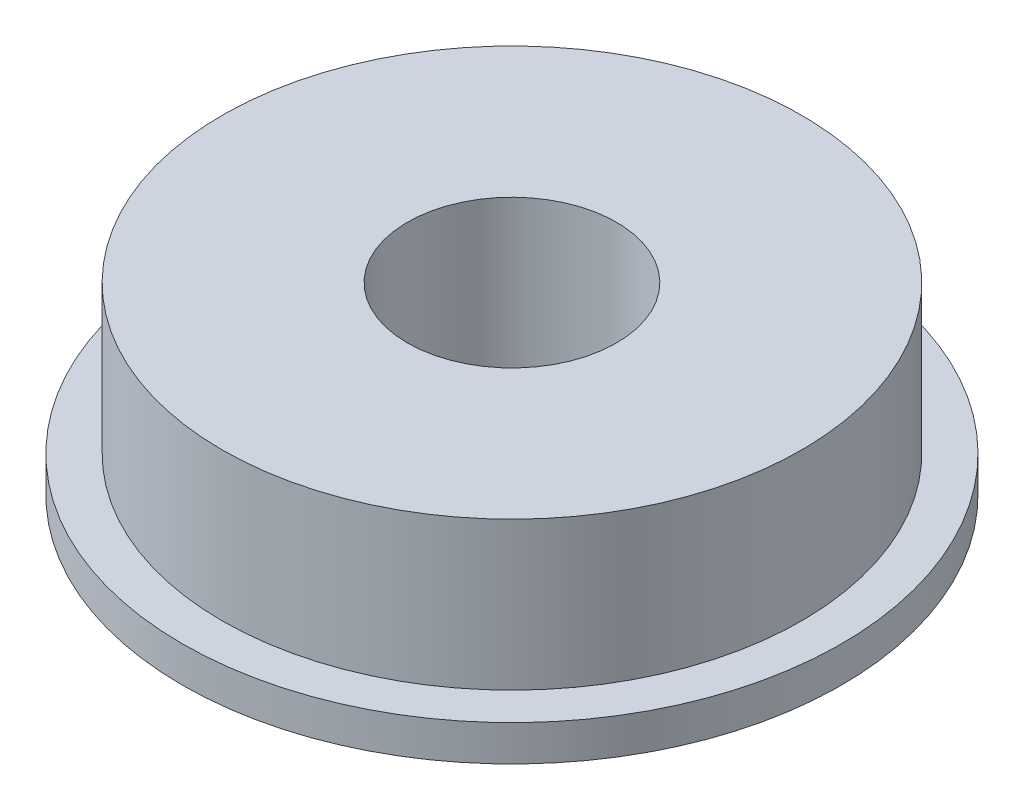
SolidWorks part; units mm, degrees
ref_plane "Front Plane" through (0, 0, 0) normal (0, 0, 1) x (1, 0, 0)
ref_plane "Top Plane" through (0, 0, 0) normal (0, 1, 0) x (1, 0, 0)
ref_plane "Right Plane" through (0, 0, 0) normal (1, 0, 0) x (0, 0, -1)
sketch "Sketch1" plane through (0, 0, 0) normal (0, 1, 0) x (1, 0, 0)
  circle A0 centre (0, 0) radius 12.51
  dimension "D1" = 25.02
extrude "Boss-Extrude1" add sketch "Sketch1" along normal blind 1.36
sketch "Sketch2" plane through (0, 1.36, 0) normal (0, 1, 0) x (1, 0, 0)
  circle A0 centre (0, 0) radius 11
  dimension "D1" = 22
extrude "Boss-Extrude2" add sketch "Sketch2" along normal blind 6.98 from surface at -1.36 starting at plane "Top Plane"
sketch "Sketch3" plane through (0, 6.98, 0) normal (0, 1, 0) x (1, 0, 0)
  circle A0 centre (0, 0) radius 3.97
  dimension "D1" = 7.94
extrude "Cut-Extrude1" cut sketch "Sketch3" against normal through all
